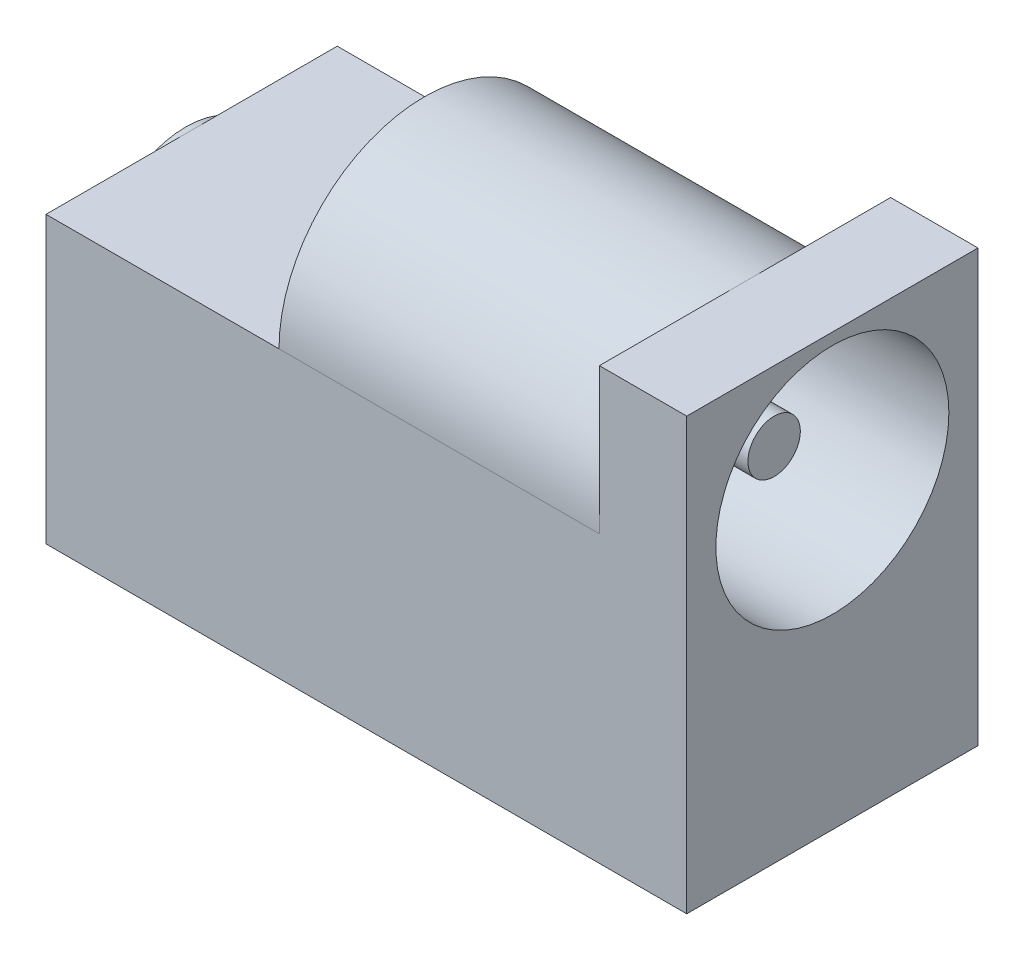
SolidWorks part; units mm, degrees
ref_plane "Alzado" through (0, 0, 0) normal (0, 0, 1) x (1, 0, 0)
ref_plane "Planta" through (0, 0, 0) normal (0, 1, 0) x (1, 0, 0)
ref_plane "Vista lateral" through (0, 0, 0) normal (1, 0, 0) x (0, 0, -1)
sketch "Croquis1" plane through (0, 0, 0) normal (1, 0, 0) x (0, 0, -1)
  line L1 (-2.5, 3.7) -> (2.5, 3.7)
  line L2 (-2.5, 3.7) -> (-2.5, -3.7)
  line L3 (-2.5, -3.7) -> (2.5, -3.7)
  line L4 (2.5, 3.7) -> (2.5, -3.7)
  line L5 (-2.5, 3.7) -> (2.5, -3.7) construction
  line L6 (-2.5, -3.7) -> (2.5, 3.7) construction
  point P0 (0, 0)
  dimension "D1" = 5
  dimension "D2" = 7.4
extrude "Extruir1" add sketch "Croquis1" along normal mid plane 1.5
sketch "Croquis2" plane through (-0.75, 0, 0) normal (-1, 0, 0) x (0, 0, 1)
  line L0 (-2.5, -3.7) -> (-2.5, 1.2)
  line L2 (2.5, -3.7) -> (2.5, 1.2)
  line L4 (-2.5, -3.7) -> (2.5, -3.7)
  line L5 (-2.5, 3.7) -> (2.5, 3.7) construction
  arc A0 (-2.5, 1.2) -> (2.5, 1.2) centre (0, 1.2) cw
extrude "Extruir2" add sketch "Croquis2" along normal blind 5.5
sketch "Croquis3" plane through (-6.25, 0, 0) normal (-1, 0, 0) x (0, 0, 1)
  line L1 (-2.5, -3.7) -> (2.5, -3.7)
  line L2 (-2.5, -3.7) -> (-2.5, 1.2)
  line L3 (-2.5, 1.2) -> (2.5, 1.2)
  line L4 (2.5, -3.7) -> (2.5, 1.2)
extrude "Extruir3" add sketch "Croquis3" along normal blind 4
sketch "Croquis4" plane through (0.75, 0, 0) normal (1, 0, 0) x (0, 0, -1)
  line L0 (2.5, 3.7) -> (-2.5, 3.7) construction
  circle A0 centre (0, 1.5) radius 2
  dimension "D1" = 4
  dimension "D2" = 0.2
extrude "Extruir4" cut sketch "Croquis4" against normal blind 6
sketch "Croquis5" plane through (-5.25, 0, 0) normal (1, 0, 0) x (0, 0, -1)
  circle A0 centre (0, 1.5) radius 0.5
  circle A1 centre (0, 1.5) radius 2 construction
  dimension "D1" = 1
extrude "Extruir5" add sketch "Croquis5" along normal blind 2
sketch "Croquis6" plane through (-3.25, 0, 0) normal (1, 0, 0) x (0, 0, -1)
  circle A0 centre (0, 1.5) radius 0.45
  dimension "D1" = 0.9
extrude "Extruir6" add sketch "Croquis6" along normal blind 3
sketch "Croquis7" plane through (-10.25, 0, 0) normal (-1, 0, 0) x (0, 0, 1)
  line L0 (-1.5, -3.7) -> (-1.5, -0.3)
  line L1 (-2.5, -3.7) -> (2.5, -3.7) construction
  line L2 (1.5, -3.7) -> (1.5, -0.3)
  line L3 (-1.5, -3.7) -> (-0.5, -3.7)
  line L4 (-0.5, -3.7) -> (-0.5, -4.7)
  line L5 (1.5, -3.7) -> (0.5, -3.7)
  line L6 (0.5, -3.7) -> (0.5, -4.7)
  line L8 (2.5, 1.2) -> (-2.5, 1.2) construction
  arc A0 (-1.5, -0.3) -> (1.5, -0.3) centre (0, -0.3) cw
  arc A1 (-0.5, -4.7) -> (0.5, -4.7) centre (0, -4.7) ccw
  point P15 (0, -3.7)
  dimension "D2" = 1
  dimension "D1" = 3
  dimension "D3" = 1
  dimension "D4" = 1
extrude "Extruir7" add sketch "Croquis7" along normal blind 0.1
sketch "Croquis8" plane through (-10.35, 0, 0) normal (-1, 0, 0) x (0, 0, 1)
  circle A0 centre (0, 0) radius 0.3855
  dimension "D1" = 0.771
extrude "Extruir8" add sketch "Croquis8" along normal blind 0.1
sketch "Croquis9" plane through (0, 0, -2.5) normal (0, 0, -1) x (-1, 0, 0)
  line L0 (-0.75, -3.7) -> (10.25, -3.7) construction
  line L1 (7.85, -3.7) -> (8.2687, -4.1187)
  line L2 (7.85, -3.7) -> (7.85, -1.3)
  line L3 (7.85, -1.3) -> (9.35, -1.3)
  line L4 (9.35, -3.7) -> (9.35, -1.3)
  line L5 (10.35, -0.3) -> (10.35, -3.7) construction
  line L6 (10.25, 1.2) -> (6.25, 1.2) construction
  line L7 (8.2687, -4.1187) -> (8.2687, -5.1974)
  line L8 (8.2687, -5.1974) -> (8.6, -5.5287)
  line L9 (8.6, -5.5287) -> (8.9313, -5.1974)
  line L10 (8.9313, -5.1974) -> (8.9313, -4.1187)
  line L11 (8.9313, -4.1187) -> (9.35, -3.7)
  line L12 (10.25, 1.2) -> (10.25, -3.7) construction
  dimension "D1" = 1
  dimension "D2" = 2.5
  dimension "D3" = 1.3187
  dimension "D4" = 1.65
  dimension "D5" = 1.4974
extrude "Extruir9" add sketch "Croquis9" along normal blind 0.1
